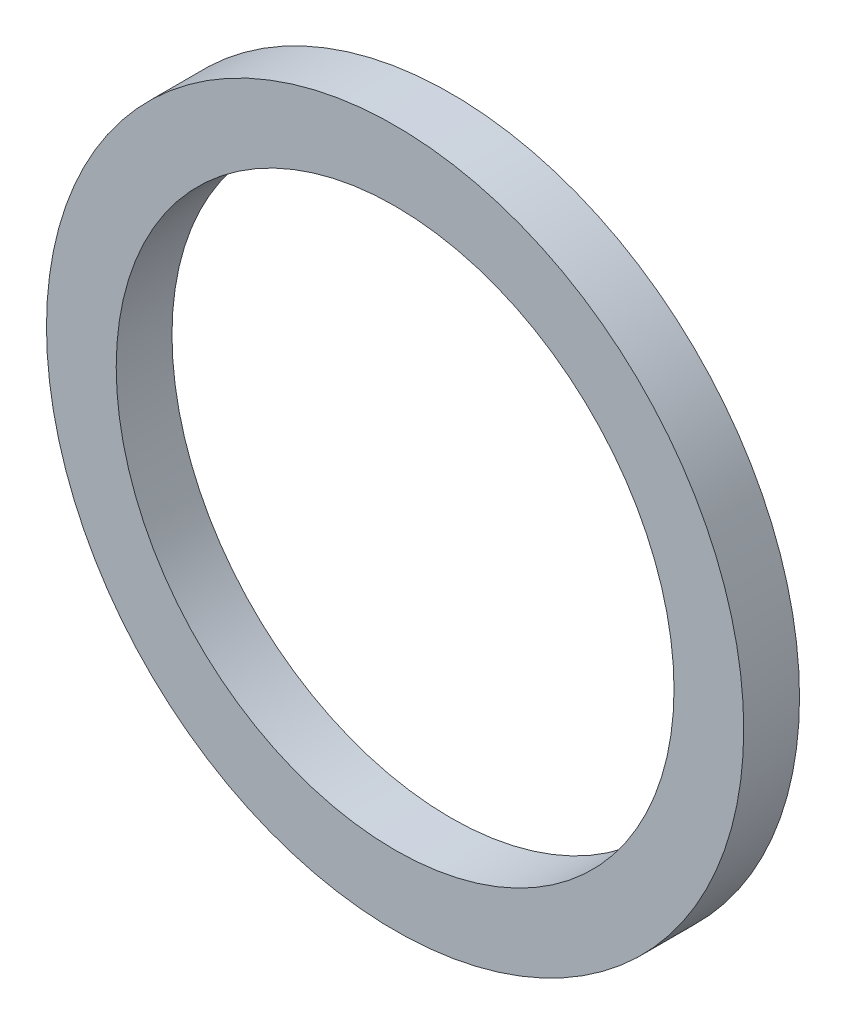
SolidWorks part; units mm, degrees
material "Nylon 101"
ref_plane "Спереди" through (0, 0, 0) normal (0, 0, 1) x (1, 0, 0)
ref_plane "Сверху" through (0, 0, 0) normal (0, 1, 0) x (1, 0, 0)
ref_plane "Справа" through (0, 0, 0) normal (1, 0, 0) x (0, 0, -1)
sketch "Эскиз1" plane through (0, 0, 0) normal (0, 0, 1) x (1, 0, 0)
  circle A0 centre (0, 0) radius 1
  circle A1 centre (0, 0) radius 1.25
  dimension "D1" = 2
  dimension "D2" = 2.5
extrude "Бобышка-Вытянуть2" add sketch "Эскиз1" along normal blind 0.2
